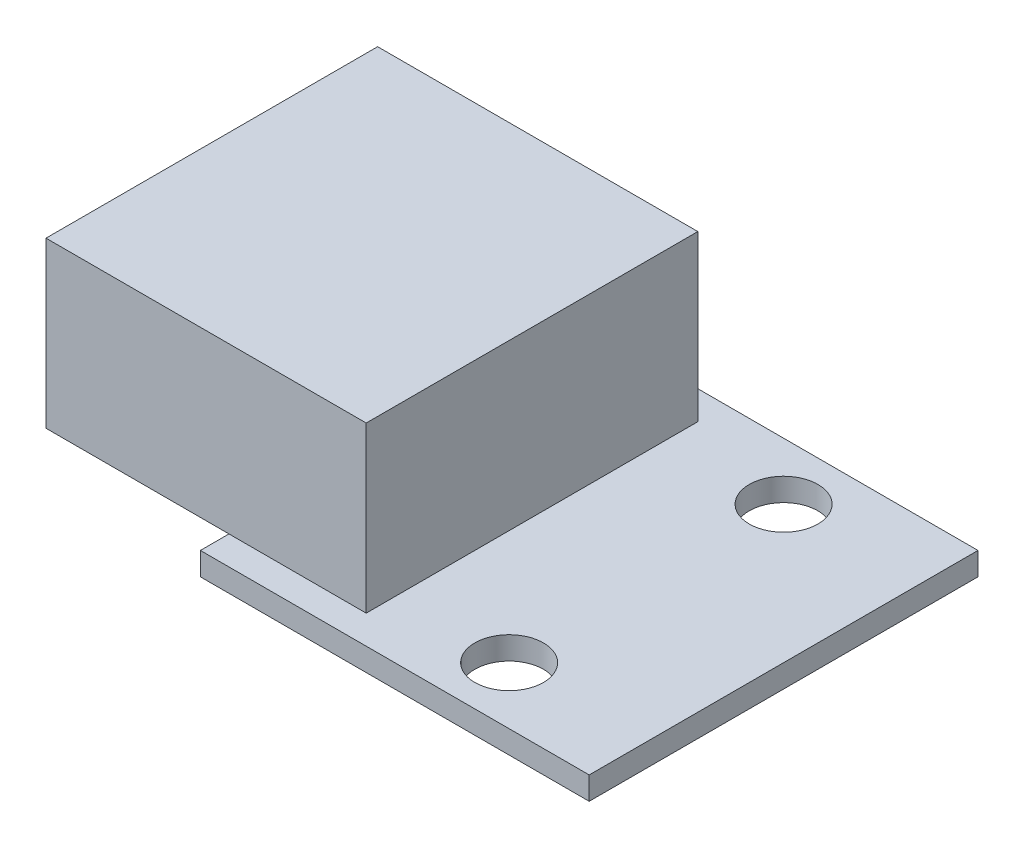
SolidWorks part; units mm, degrees
ref_plane "Front Plane" through (0, 0, 0) normal (0, 0, 1) x (1, 0, 0)
ref_plane "Top Plane" through (0, 0, 0) normal (0, 1, 0) x (1, 0, 0)
ref_plane "Right Plane" through (0, 0, 0) normal (1, 0, 0) x (0, 0, -1)
sketch "Sketch1" plane through (0, 0, 0) normal (0, 1, 0) x (1, 0, 0)
  line L0 (-17, 8.5) -> (0, 8.5) construction
  line L1 (0, 0) -> (-17, 0)
  line L2 (0, 0) -> (0, 17)
  line L3 (0, 17) -> (-17, 17)
  line L4 (-17, 0) -> (-17, 17)
  line L5 (-6, 2.5) -> (-6, 14.5) construction
  circle A0 centre (-6, 14.5) radius 1.5
  circle A1 centre (-6, 2.5) radius 1.5
  point P10 (-6, 8.5)
  dimension "D3" = 3
  dimension "D4" = 3
  dimension "D1" = 17
  dimension "D2" = 17
  dimension "D5" = 6
  dimension "D6" = 11
extrude "Boss-Extrude1" add sketch "Sketch1" along normal blind 1
ref_plane "Plane1" through (-25, 0, 0) normal (-1, 0, 0) x (0, 0, 1)
sketch "Sketch2" plane through (-25, 0, 0) normal (-1, 0, 0) x (0, 0, 1)
  line L0 (-8.5, 1) -> (-8.5, 8.2) construction
  line L1 (-17, 1) -> (0, 1) construction
  line L3 (-15.75, 1) -> (-1.25, 1)
  line L4 (-15.75, 1) -> (-15.75, 8.2)
  line L5 (-15.75, 8.2) -> (-1.25, 8.2)
  line L6 (-1.25, 1) -> (-1.25, 8.2)
  dimension "D1" = 7.25
  dimension "D2" = 7.25
  dimension "D3" = 7.2
extrude "Boss-Extrude2" add sketch "Sketch2" against normal blind 14
sketch "Sketch3" plane through (-25, 0, 0) normal (-1, 0, 0) x (0, 0, 1)
  line L8 (-14.75, 7.2) -> (-14.75, 2)
  line L9 (-14.75, 2) -> (-2.25, 2)
  line L10 (-2.25, 2) -> (-2.25, 7.2)
  line L11 (-2.25, 7.2) -> (-14.75, 7.2)
  line L12 (-14.75, 7.2) -> (-14.75, 2)
  line L13 (-14.75, 2) -> (-2.25, 2)
  line L14 (-2.25, 2) -> (-2.25, 7.2)
  line L15 (-2.25, 7.2) -> (-14.75, 7.2)
  dimension "D1" = 1
extrude "Cut-Extrude1" cut sketch "Sketch3" against normal blind 10
